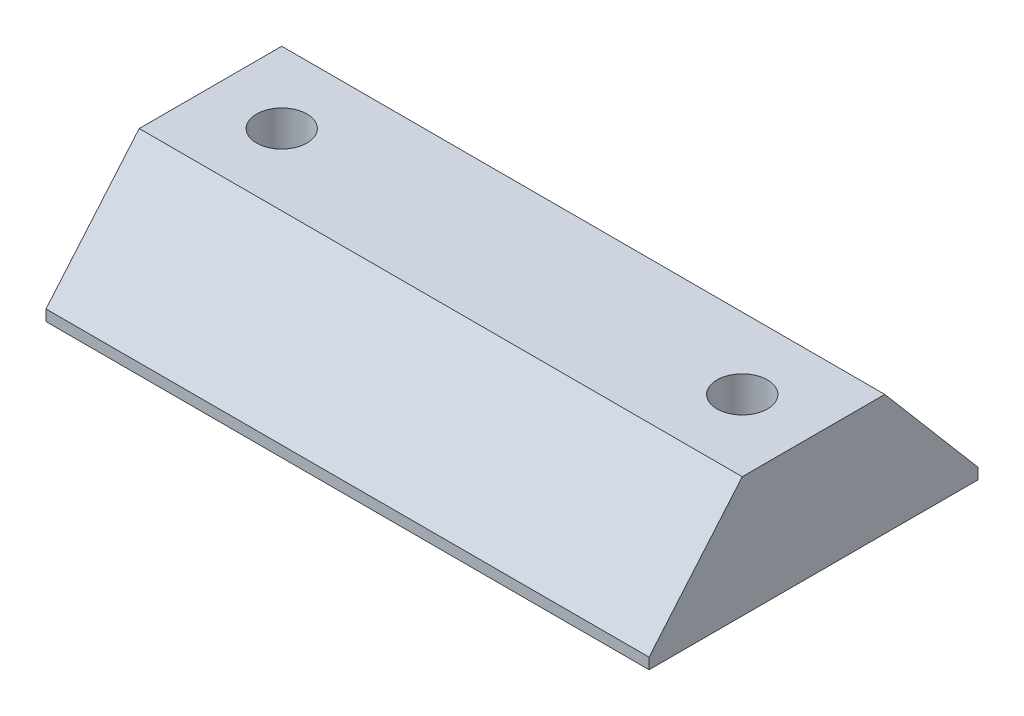
SolidWorks part; units mm, degrees
ref_plane "Front Plane" through (0, 0, 0) normal (0, 0, 1) x (1, 0, 0)
ref_plane "Top Plane" through (0, 0, 0) normal (0, 1, 0) x (1, 0, 0)
ref_plane "Right Plane" through (0, 0, 0) normal (1, 0, 0) x (0, 0, -1)
sketch "Sketch2" plane through (0, 0, 0) normal (0, 1, 0) x (1, 0, 0)
  line L1 (0, 0) -> (55, 0)
  line L2 (0, 0) -> (0, 30)
  line L3 (0, 30) -> (55, 30)
  line L4 (55, 0) -> (55, 30)
  dimension "D1" = 30
  dimension "D2" = 55
extrude "Boss-Extrude1" add sketch "Sketch2" along normal blind 11
chamfer "Chamfer1" distance 10 distance2 8.5 2 edges at (27.5, 11, -30) (27.5, 11, 0)
sketch "Sketch3" plane through (0, 11, 0) normal (0, 1, 0) x (1, 0, 0)
  line L0 (0, 21.5) -> (0, 8.5) construction
  line L1 (55, 21.5) -> (0, 21.5) construction
  circle A0 centre (6.5, 15) radius 2.3
  circle A1 centre (48.5, 15) radius 2.3
  dimension "D1" = 4.6
  dimension "D2" = 4.6
  dimension "D3" = 42
  dimension "D4" = 6.5
  dimension "D5" = 6.5
extrude "Cut-Extrude1" cut sketch "Sketch3" against normal up to next
sketch "Sketch4" plane through (0, 0, 0) normal (0, -1, 0) x (1, 0, 0)
  line L1 (0, 0.85) -> (55, 0.85) construction
  line L2 (16.5, -10.25) -> (38.5, -10.25)
  line L3 (16.5, -10.25) -> (16.5, -18.05)
  line L4 (16.5, -18.05) -> (38.5, -18.05)
  line L7 (38.5, -10.25) -> (38.5, -18.05)
  dimension "D1" = 7.8
  dimension "D2" = 11.1
extrude "Boss-Extrude2" add sketch "Sketch4" along normal blind 3
